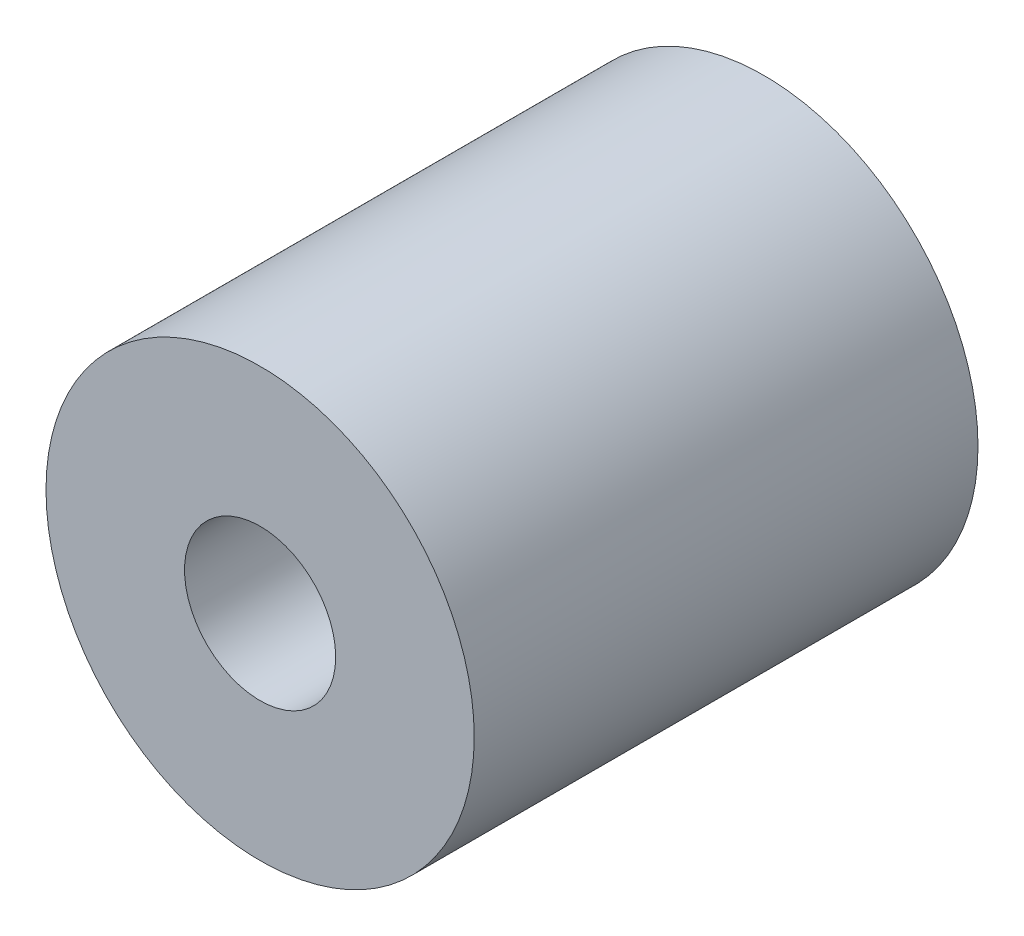
SolidWorks part; units mm, degrees
ref_plane "Front Plane" through (0, 0, 0) normal (0, 0, 1) x (1, 0, 0)
ref_plane "Top Plane" through (0, 0, 0) normal (0, 1, 0) x (1, 0, 0)
ref_plane "Right Plane" through (0, 0, 0) normal (1, 0, 0) x (0, 0, -1)
sketch "Sketch1" plane through (0, 0, 0) normal (0, 0, 1) x (1, 0, 0)
  circle A0 centre (0, 0) radius 8.5
  dimension "D1" = 17
extrude "Boss-Extrude1" add sketch "Sketch1" along normal blind 20
sketch "Sketch2" plane through (0, 0, 20) normal (0, 0, 1) x (1, 0, 0)
  circle A0 centre (0, 0) radius 3
  dimension "D1" = 6
extrude "Cut-Extrude1" cut sketch "Sketch2" against normal through all
